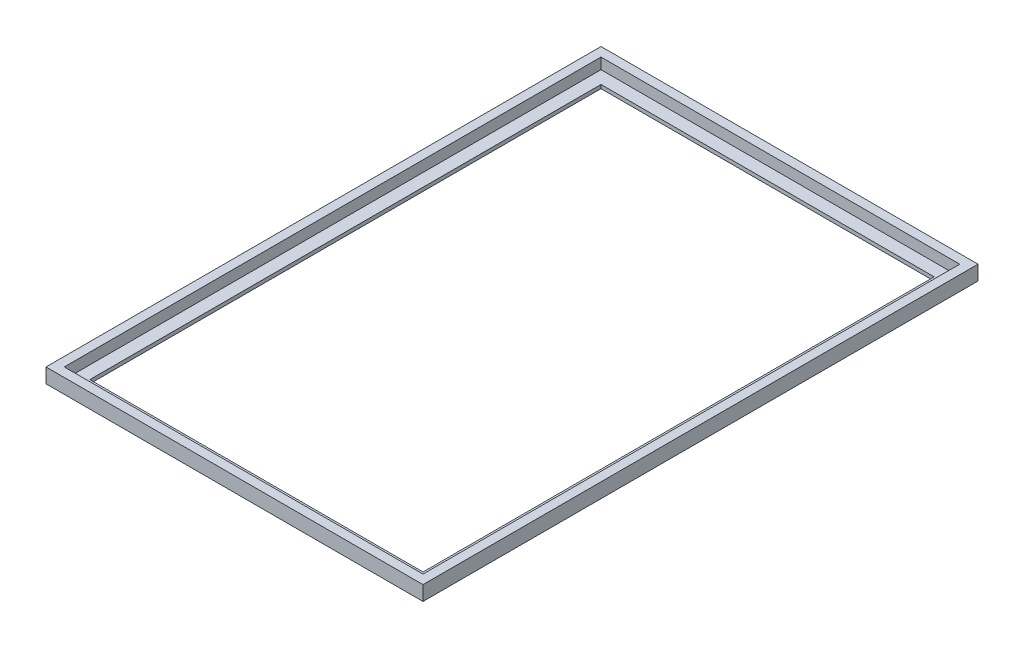
SolidWorks part; units mm, degrees
ref_plane "Front Plane" through (0, 0, 0) normal (0, 0, 1) x (1, 0, 0)
ref_plane "Top Plane" through (0, 0, 0) normal (0, 1, 0) x (1, 0, 0)
ref_plane "Right Plane" through (0, 0, 0) normal (1, 0, 0) x (0, 0, -1)
sketch "Sketch1" plane through (0, 0, 0) normal (0, 1, 0) x (1, 0, 0)
  line L0 (-91.25, 140) -> (-91.25, 152) construction
  line L1 (103.25, -152) -> (-103.25, -152)
  line L2 (103.25, -152) -> (103.25, 152)
  line L3 (103.25, 152) -> (-103.25, 152)
  line L4 (-103.25, -152) -> (-103.25, 152)
  line L5 (103.25, -152) -> (-103.25, 152) construction
  line L6 (103.25, 152) -> (-103.25, -152) construction
  line L7 (91.25, -140) -> (-91.25, -140)
  line L8 (91.25, -140) -> (91.25, 140)
  line L9 (91.25, 140) -> (-91.25, 140)
  line L10 (-91.25, -140) -> (-91.25, 140)
  line L11 (91.25, -140) -> (-91.25, 140) construction
  line L12 (91.25, 140) -> (-91.25, -140) construction
  line L13 (-91.25, 140) -> (-103.25, 140) construction
  point P0 (0, 0)
  point P6 (0, 0)
  dimension "D1" = 304
  dimension "D2" = 12
  dimension "D3" = 206.5
extrude "Boss-Extrude1" add sketch "Sketch1" along normal blind 2
sketch "Sketch2" plane through (0, 2, 0) normal (0, 1, 0) x (1, 0, 0)
  line L0 (-98.25, 147) -> (-98.25, -147)
  line L1 (-98.25, -147) -> (98.25, -147)
  line L2 (98.25, -147) -> (98.25, 147)
  line L3 (98.25, 147) -> (-98.25, 147)
  line L4 (-103.25, 152) -> (-103.25, -152)
  line L5 (-103.25, -152) -> (103.25, -152)
  line L6 (103.25, -152) -> (103.25, 152)
  line L7 (103.25, 152) -> (-103.25, 152)
  line L8 (-103.25, 152) -> (-103.25, -152)
  line L9 (-103.25, -152) -> (103.25, -152)
  line L10 (103.25, -152) -> (103.25, 152)
  line L11 (103.25, 152) -> (-103.25, 152)
  dimension "D1" = 0
  dimension "D2" = 5
extrude "Boss-Extrude2" add sketch "Sketch2" along normal blind 6
